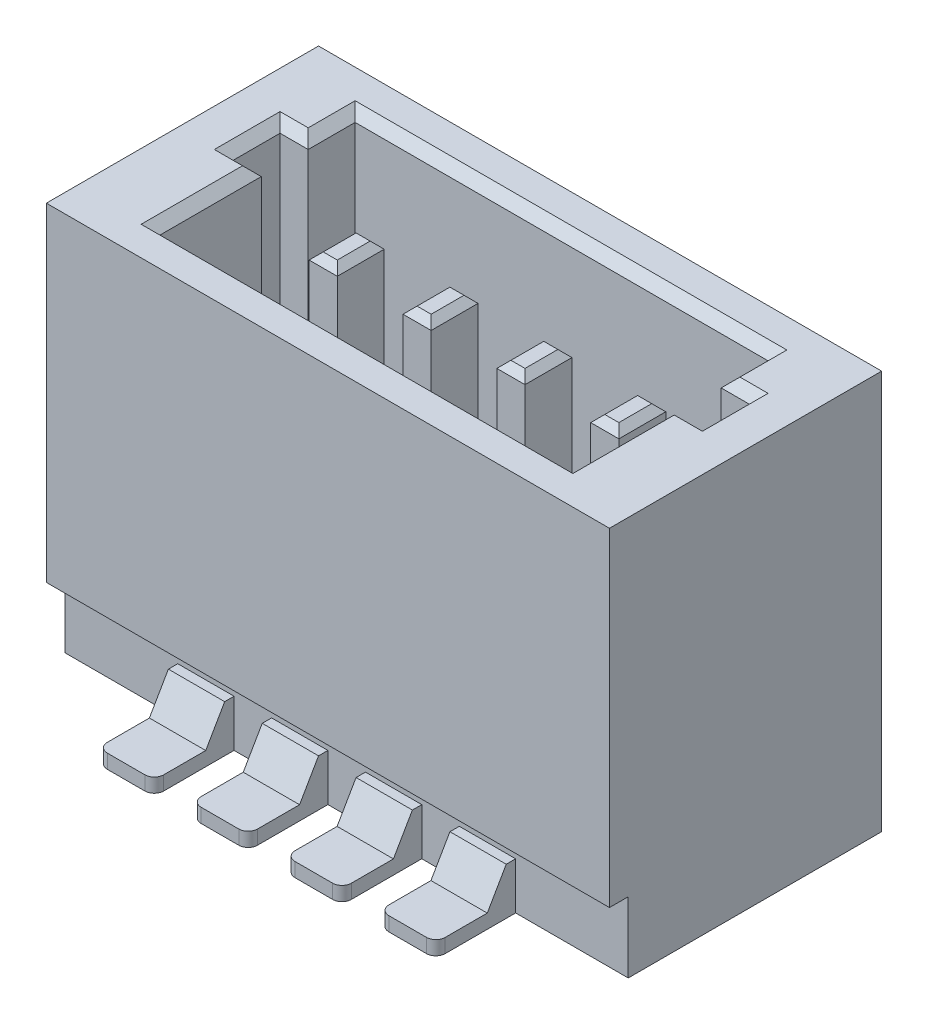
SolidWorks part; units mm, degrees
material "ABS"
ref_plane "Front Plane" through (0, 0, 0) normal (0, 0, 1) x (1, 0, 0)
ref_plane "Top Plane" through (0, 0, 0) normal (0, 1, 0) x (1, 0, 0)
ref_plane "Right Plane" through (0, 0, 0) normal (1, 0, 0) x (0, 0, -1)
sketch "Sketch1" plane through (0, 0, 0) normal (0, 1, 0) x (1, 0, 0)
  line L1 (-3, -1.45) -> (3, -1.45)
  line L2 (-3, -1.45) -> (-3, 1.45)
  line L3 (-3, 1.45) -> (3, 1.45)
  line L4 (3, -1.45) -> (3, 1.45)
  line L5 (-3, -1.45) -> (3, 1.45) construction
  line L6 (-3, 1.45) -> (3, -1.45) construction
  point P0 (0, 0)
  dimension "D1" = 2.9
  dimension "D2" = 6
extrude "Boss-Extrude1" add sketch "Sketch1" along normal blind 4.25
sketch "Sketch2" plane through (0, 4.25, 0) normal (0, 1, 0) x (1, 0, 0)
  line L0 (-3, 0) -> (0, 0) construction
  line L1 (-3, 1.45) -> (-3, -1.45) construction
  line L2 (0, 0) -> (0, 1.45) construction
  line L3 (3, 1.45) -> (-3, 1.45) construction
  line L4 (2.2, 0.04) -> (2.5, 0.04)
  line L5 (-2.2, -1.04) -> (2.2, -1.04)
  line L6 (-2.2, -1.04) -> (-2.2, 0.04)
  line L7 (-2.2, 1.04) -> (2.2, 1.04)
  line L8 (2.2, -1.04) -> (2.2, 0.04)
  line L9 (-2.2, -1.04) -> (2.2, 1.04) construction
  line L10 (-2.2, 1.04) -> (2.2, -1.04) construction
  line L11 (-2.2, 0.54) -> (-2.5, 0.54)
  line L13 (-2.2, 0.04) -> (-2.5, 0.04)
  line L14 (-2.5, 0.54) -> (-2.5, 0.04)
  line L15 (2.5, 0.54) -> (2.5, 0.04)
  line L16 (2.2, 0.54) -> (2.5, 0.54)
  line L17 (-2.2, 0.54) -> (-2.2, 1.04)
  line L18 (2.2, 0.54) -> (2.2, 1.04)
  dimension "D1" = 4.4
  dimension "D2" = 2.08
  dimension "D3" = 0.5
  dimension "D4" = 1
  dimension "D5" = 2.5
extrude "Cut-Extrude1" cut sketch "Sketch2" against normal blind 3.2
sketch "Sketch4" plane through (0, 0, 1.45) normal (0, 0, 1) x (1, 0, 0)
  line L0 (3, 4.25) -> (3, 0) construction
  line L1 (-3, 0) -> (3, 0)
  line L2 (-3, 0) -> (-3, 0.75)
  line L3 (-3, 0.75) -> (3, 0.75)
  line L4 (3, 0) -> (3, 0.75)
  dimension "D1" = 0.75
extrude "Cut-Extrude2" cut sketch "Sketch4" against normal blind 0.2
sketch "Sketch5" plane through (0, 0, 1.25) normal (0, 0, 1) x (1, 0, 0)
  line L0 (0, 4.25) -> (0, 0) construction
  line L1 (-3, 4.25) -> (3, 4.25) construction
  line L2 (-3, 0) -> (3, 0) construction
  line L3 (-0.2, 0) -> (-0.8, 0)
  line L4 (-0.2, 0) -> (-0.2, 0.5)
  line L5 (-0.2, 0.5) -> (-0.8, 0.5)
  line L6 (-0.8, 0) -> (-0.8, 0.5)
  line L7 (-1.8, 0) -> (-1.8, 0.5)
  line L8 (-1.2, 0.5) -> (-1.8, 0.5)
  line L9 (-1.2, 0) -> (-1.8, 0)
  line L10 (-1.2, 0) -> (-1.2, 0.5)
  line L11 (1.2, 0) -> (1.2, 0.5)
  line L12 (1.2, 0) -> (1.8, 0)
  line L13 (1.8, 0) -> (1.8, 0.5)
  line L14 (1.2, 0.5) -> (1.8, 0.5)
  line L15 (0.2, 0) -> (0.2, 0.5)
  line L16 (0.2, 0) -> (0.8, 0)
  line L17 (0.2, 0.5) -> (0.8, 0.5)
  line L18 (0.8, 0) -> (0.8, 0.5)
  point P11 (-0.5, 0.5)
  dimension "D1" = 0.6
  dimension "D2" = 0.5
  dimension "D3" = 0.5
  dimension "D4" = 2
extrude "Boss-Extrude2" add sketch "Sketch5" along normal blind 0.85
sketch "Sketch6" plane through (1.8, 0, 0) normal (1, 0, 0) x (0, 0, -1)
  line L0 (-1.35, 0.5) -> (-1.5521, 0.15)
  line L1 (-2.1, 0.5) -> (-1.25, 0.5) construction
  line L2 (-1.5521, 0.15) -> (-2.1, 0.15)
  line L3 (-2.1, 0) -> (-2.1, 0.5) construction
  line L4 (-2.1, 0.15) -> (-2.1, 0.5)
  line L5 (-2.1, 0.5) -> (-1.35, 0.5)
  line L6 (-1.25, 0) -> (-1.25, 0.75) construction
  line L7 (-2.1, 0) -> (-1.25, 0) construction
  dimension "D1" = 60
  dimension "D2" = 0.1
  dimension "D3" = 0.15
extrude "Cut-Extrude3" cut sketch "Sketch6" against normal through all
sketch "Sketch7" plane through (0, 1.05, 0) normal (0, 1, 0) x (1, 0, 0)
  line L0 (0, 1.04) -> (0, 0) construction
  line L1 (2.2, 1.04) -> (-2.2, 1.04) construction
  line L2 (0, 0) -> (-2.2, 0) construction
  line L3 (-2.2, 0.04) -> (-2.2, -1.04) construction
  line L4 (-1.35, 0.5) -> (-1.65, 0.5)
  line L5 (-0.35, 0) -> (-0.65, 0)
  line L6 (-0.35, 0) -> (-0.35, 0.5)
  line L7 (-0.35, 0.5) -> (-0.65, 0.5)
  line L8 (-0.65, 0) -> (-0.65, 0.5)
  line L9 (-1.65, 0) -> (-1.65, 0.5)
  line L10 (-1.35, 0) -> (-1.65, 0)
  line L11 (-1.35, 0) -> (-1.35, 0.5)
  line L12 (1.35, 0) -> (1.65, 0)
  line L13 (1.35, 0) -> (1.35, 0.5)
  line L14 (1.65, 0) -> (1.65, 0.5)
  line L15 (1.35, 0.5) -> (1.65, 0.5)
  line L16 (0.35, 0) -> (0.35, 0.5)
  line L17 (0.35, 0) -> (0.65, 0)
  line L18 (0.65, 0) -> (0.65, 0.5)
  line L19 (0.35, 0.5) -> (0.65, 0.5)
  point P12 (-0.5, 0.5)
  dimension "D1" = 0.5
  dimension "D2" = 0.3
  dimension "D3" = 0.5
  dimension "D4" = 2
extrude "Boss-Extrude3" add sketch "Sketch7" along normal offset from surface (2.7 mm away) 0.5 up to face at (0, 4.25, -0.1933)
chamfer "Chamfer1" distance 0.075 angle 45 16 edges at (1.35, 3.75, -0.25) (1.5, 3.75, -0.5) (1.65, 3.75, -0.25) (1.5, 3.75, 0) (0.5, 3.75, 0) (0.35, 3.75, -0.25) (0.5, 3.75, -0.5) (0.65, 3.75, -0.25) (-0.35, 3.75, -0.25) (-0.5, 3.75, 0) (-0.65, 3.75, -0.25) (-0.5, 3.75, -0.5) (-1.35, 3.75, -0.25) (-1.5, 3.75, 0) (-1.65, 3.75, -0.25) (-1.5, 3.75, -0.5)
fillet "Fillet1" radius 0.1 8 edges at (-1.8, 0.075, 2.1) (-1.2, 0.075, 2.1) (-0.8, 0.075, 2.1) (-0.2, 0.075, 2.1) (0.2, 0.075, 2.1) (0.8, 0.075, 2.1) (1.2, 0.075, 2.1) (1.8, 0.075, 2.1)
chamfer "Chamfer2" distance 0.1 angle 45 12 edges at (2.2, 4.25, -0.79) (2.35, 4.25, -0.54) (2.5, 4.25, -0.29) (2.35, 4.25, -0.04) (2.2, 4.25, 0.5) (0, 4.25, 1.04) (0, 4.25, -1.04) (-2.2, 4.25, -0.79) (-2.35, 4.25, -0.54) (-2.5, 4.25, -0.29) (-2.35, 4.25, -0.04) (-2.2, 4.25, 0.5)
